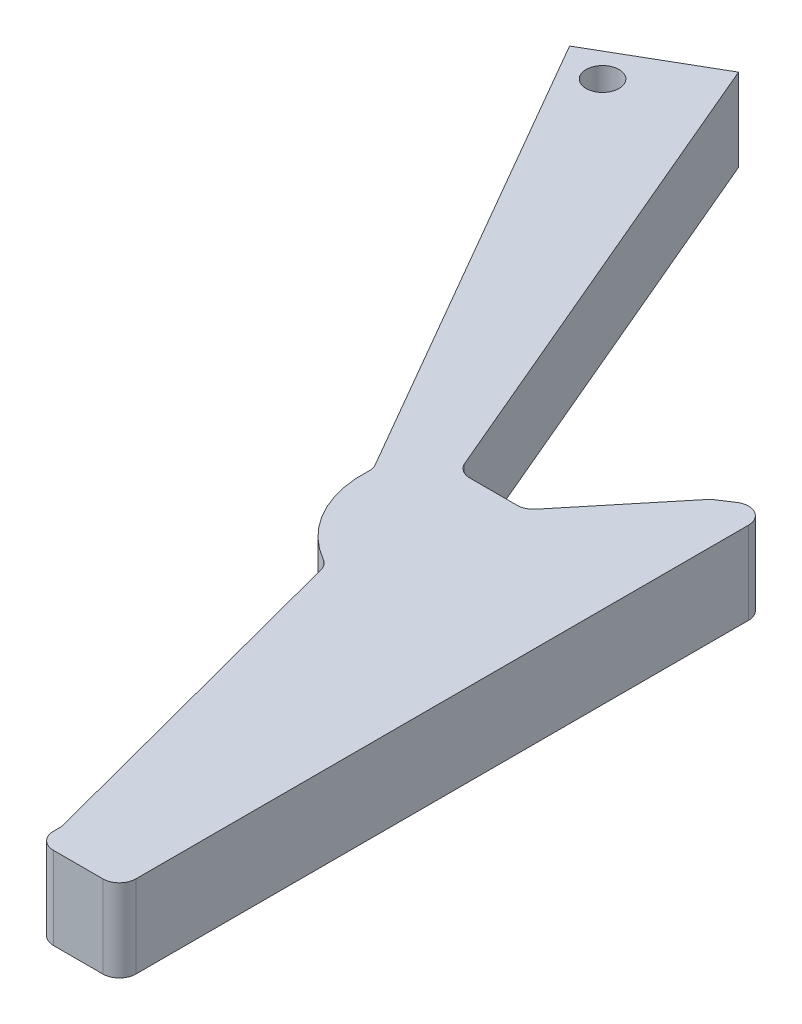
SolidWorks part; units mm, degrees
ref_plane "Front Plane" through (0, 0, 0) normal (0, 0, 1) x (1, 0, 0)
ref_plane "Top Plane" through (0, 0, 0) normal (0, 1, 0) x (1, 0, 0)
ref_plane "Right Plane" through (0, 0, 0) normal (1, 0, 0) x (0, 0, -1)
sketch "Sketch1" plane through (0, 0, 0) normal (0, 1, 0) x (1, 0, 0)
  line L0 (19.6705, 15.8093) -> (-13.0782, 15.8093) construction
  line L1 (13.9972, 15.8093) -> (1.0068, 8.3093)
  line L2 (1.0068, 8.3093) -> (33.5068, -47.9823)
  line L3 (13.9972, 15.8093) -> (39.0039, -43.103)
  line L4 (39.0039, -43.103) -> (47.0039, -43.103)
  line L5 (47.0039, -43.103) -> (57.1589, -30.7387)
  line L6 (57.1589, -30.7387) -> (62.1731, -27.4436)
  line L7 (62.1731, -27.4436) -> (62.1731, -107.4436)
  line L8 (62.1731, -107.4436) -> (52.1731, -107.4436)
  line L9 (52.1731, -107.4436) -> (52.1731, -104.4436)
  line L10 (52.1731, -104.4436) -> (40.7177, -60.9261)
  arc A0 (33.5068, -47.9823) -> (40.7177, -60.9261) centre (46.4443, -49.2553) ccw
  circle A1 centre (6.4709, 6.8452) radius 2
  dimension "D14" = 13
  dimension "D15" = 4
  dimension "D1" = 15
  dimension "D2" = 30
  dimension "D3" = 90
  dimension "D4" = 65
  dimension "D5" = 83
  dimension "D6" = 64
  dimension "D7" = 8
  dimension "D8" = 16
  dimension "D9" = 6
  dimension "D10" = 80
  dimension "D11" = 10
  dimension "D12" = 3
  dimension "D13" = 45
  dimension "D16" = 4
  dimension "D17" = 4
extrude "Boss-Extrude1" add sketch "Sketch1" along normal blind 10
fillet "Fillet1" radius 2 9 edges at (62.1731, 5, 27.4436) (57.1589, 5, 30.7387) (47.0039, 5, 43.103) (39.0039, 5, 43.103) (33.5068, 5, 47.9823) (40.7177, 5, 60.9261) (52.1731, 5, 104.4436) (52.1731, 5, 107.4436) (62.1731, 5, 107.4436)
